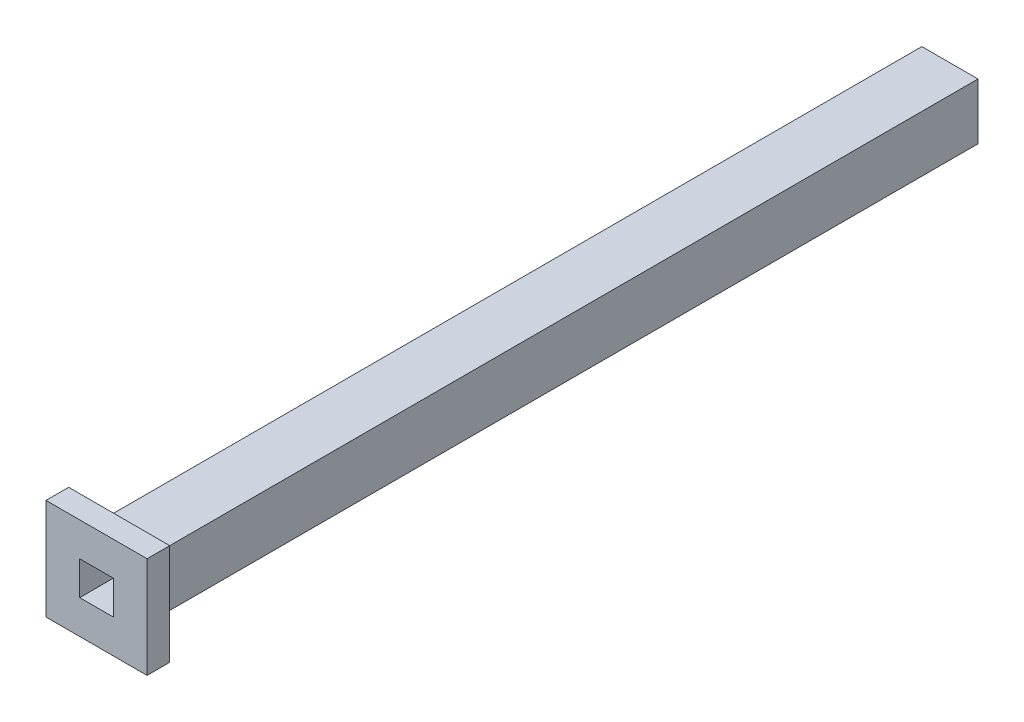
SolidWorks part; units mm, degrees
ref_plane "Front Plane" through (0, 0, 0) normal (0, 0, 1) x (1, 0, 0)
ref_plane "Top Plane" through (0, 0, 0) normal (0, 1, 0) x (1, 0, 0)
ref_plane "Right Plane" through (0, 0, 0) normal (1, 0, 0) x (0, 0, -1)
sketch "Sketch1" plane through (0, 0, 0) normal (0, 0, 1) x (1, 0, 0)
  line L1 (0, 0) -> (6, 0)
  line L2 (0, 0) -> (0, 6)
  line L3 (0, 6) -> (6, 6)
  line L4 (6, 0) -> (6, 6)
  line L5 (-2, 8) -> (8, 8)
  line L6 (-2, 8) -> (-2, -2)
  line L7 (-2, -2) -> (8, -2)
  line L8 (8, 8) -> (8, -2)
  dimension "D1" = 6
  dimension "D2" = 6
  dimension "D3" = 2
  dimension "D4" = 2
  dimension "D5" = 2
  dimension "D6" = 2
extrude "Boss-Extrude1" add sketch "Sketch1" along normal blind 2.54
sketch "Sketch2" plane through (0, 0, 0) normal (0, 0, -1) x (-1, 0, 0)
  line L0 (-8, 8) -> (-8, -2)
  line L1 (-8, -2) -> (2, -2)
  line L2 (2, -2) -> (2, -4)
  line L3 (2, -4) -> (-10, -4)
  line L4 (-10, -4) -> (-10, 8)
  line L5 (-10, 8) -> (-8, 8)
  dimension "D1" = 2
  dimension "D2" = 2
extrude "Boss-Extrude4" add sketch "Sketch2" against normal blind 2.54
sketch "Sketch5" plane through (0, 0, 0) normal (0, 0, -1) x (-1, 0, 0)
  line L0 (-6, 6) -> (-6, 0)
  line L1 (-6, 0) -> (0, 0)
  line L2 (0, 0) -> (0, -2)
  line L3 (0, -2) -> (-8, -2)
  line L4 (-8, -2) -> (-8, 6)
  line L5 (-8, 6) -> (-6, 6)
  dimension "D1" = 2
  dimension "D2" = 2
extrude "Cut-Extrude4" cut sketch "Sketch5" against normal blind 2.54
sketch "Sketch6" plane through (0, 0, 0) normal (0, 0, -1) x (-1, 0, 0)
  line L0 (-10, 8) -> (-10, -4)
  line L1 (-10, -4) -> (2, -4)
  line L2 (2, -4) -> (2, -6)
  line L3 (2, -6) -> (-12, -6)
  line L4 (-12, -6) -> (-12, 8)
  line L5 (-12, 8) -> (-10, 8)
  dimension "D1" = 2
  dimension "D2" = 2
  dimension "D3" = 12
extrude "Boss-Extrude6" add sketch "Sketch6" against normal blind 2.54
sketch "Sketch7" plane through (0, 0, 0) normal (0, 0, -1) x (-1, 0, 0)
  line L0 (-12, 8) -> (2, 8)
  line L1 (2, 8) -> (2, -6)
  line L2 (2, -6) -> (4, -6)
  line L3 (4, -6) -> (4, 10)
  line L4 (4, 10) -> (-12, 10)
  line L5 (-12, 10) -> (-12, 8)
  dimension "D1" = 2
  dimension "D2" = 2
extrude "Boss-Extrude7" add sketch "Sketch7" against normal blind 2.54
sketch "Sketch8" plane through (0, 0, 0) normal (0, 0, -1) x (-1, 0, 0)
  line L0 (-12, 10) -> (4, 10)
  line L1 (4, 10) -> (4, -6)
  line L2 (4, -6) -> (-12, -6)
  line L3 (-12, -6) -> (-12, 10)
  line L5 (-10, 8) -> (2, 8)
  line L6 (-10, 8) -> (-10, -4)
  line L7 (-10, -4) -> (2, -4)
  line L8 (2, 8) -> (2, -4)
  dimension "D1" = 2
  dimension "D2" = 2
  dimension "D3" = 2
  dimension "D4" = 2
extrude "Cut-Extrude5" cut sketch "Sketch8" against normal blind 0.5
sketch "Sketch9" plane through (0, 0, 0) normal (0, 0, -1) x (-1, 0, 0)
  line L1 (-8, 6) -> (0, 6)
  line L2 (-8, 6) -> (-8, -2)
  line L3 (-8, -2) -> (0, -2)
  line L4 (0, 6) -> (0, -2)
extrude "Boss-Extrude8" add sketch "Sketch9" along normal blind 0.5 separate body
sketch "Sketch10" plane through (0, 0, 0) normal (0, 0, -1) x (-1, 0, 0)
  line L1 (-10, 8) -> (2, 8)
  line L2 (-10, 8) -> (-10, -4)
  line L3 (-10, -4) -> (2, -4)
  line L4 (2, 8) -> (2, -4)
  line L5 (-8, 6) -> (0, 6)
  line L6 (-8, 6) -> (-8, -2)
  line L7 (-8, -2) -> (0, -2)
  line L8 (0, 6) -> (0, -2)
extrude "Cut-Extrude6" cut sketch "Sketch10" against normal blind 10
sketch "Sketch11" plane through (0, 0, 2.54) normal (0, 0, 1) x (1, 0, 0)
  line L1 (-4, 10) -> (12, 10)
  line L2 (-4, 10) -> (-4, -6)
  line L3 (-4, -6) -> (12, -6)
  line L4 (12, 10) -> (12, -6)
  line L5 (0, 6) -> (8, 6)
  line L6 (0, 6) -> (0, -2)
  line L7 (0, -2) -> (8, -2)
  line L8 (8, 6) -> (8, -2)
extrude "Boss-Extrude9" add sketch "Sketch11" along normal blind 2
sketch "Sketch13" plane through (0, 0, -0.5) normal (0, 0, -1) x (-1, 0, 0)
  line L1 (-8, 6) -> (0, 6)
  line L2 (-8, 6) -> (-8, -2)
  line L3 (-8, -2) -> (0, -2)
  line L4 (0, 6) -> (0, -2)
extrude "Cut-Extrude7" cut sketch "Sketch13" against normal blind 2
sketch "Sketch14" plane through (0, 0, 2.54) normal (0, 0, -1) x (-1, 0, 0)
  line L5 (-7, 5) -> (-1, 5)
  line L6 (-7, 5) -> (-7, -1)
  line L7 (-7, -1) -> (-1, -1)
  line L8 (-1, 5) -> (-1, -1)
  line L9 (-9, 7) -> (1, 7)
  line L10 (-9, 7) -> (-9, -3)
  line L11 (-9, -3) -> (1, -3)
  line L12 (1, 7) -> (1, -3)
  dimension "D5" = 6
extrude "Cut-Extrude8" cut sketch "Sketch14" against normal blind 2
sketch "Sketch16" plane through (0, 0, 2.54) normal (0, 0, -1) x (-1, 0, 0)
  line L0 (2, 8) -> (2, -4) construction
  line L1 (-10, 8) -> (2, 8)
  line L2 (-10, 8) -> (-10, -4)
  line L3 (-10, -4) -> (2, -4)
  line L4 (2, 8) -> (2, -4)
  line L6 (-11, 9) -> (3, 9)
  line L7 (-11, 9) -> (-11, -5)
  line L8 (-11, -5) -> (3, -5)
  line L9 (3, 9) -> (3, -5)
  dimension "D1" = 1
  dimension "D2" = 1
  dimension "D3" = 1
  dimension "D4" = 1
extrude "Cut-Extrude12" cut sketch "Sketch16" along normal blind 10
sketch "Sketch17" plane through (0, 0, 0.5) normal (0, 0, -1) x (-1, 0, 0)
  line L1 (-12, 10) -> (4, 10)
  line L2 (-12, 10) -> (-12, -6)
  line L3 (-12, -6) -> (4, -6)
  line L4 (4, 10) -> (4, -6)
  line L5 (-13, 11) -> (5, 11)
  line L6 (-13, 11) -> (-13, -7)
  line L7 (-13, -7) -> (5, -7)
  line L8 (5, 11) -> (5, -7)
  dimension "D1" = 1
  dimension "D2" = 1
  dimension "D3" = 1
  dimension "D4" = 1
extrude "Boss-Extrude10" add sketch "Sketch17" against normal blind 4
sketch "Sketch18" plane through (0, 0, 4.54) normal (0, 0, 1) x (1, 0, 0)
  line L1 (-4, 10) -> (12, 10)
  line L2 (-4, 10) -> (-4, -6)
  line L3 (-4, -6) -> (12, -6)
  line L4 (12, 10) -> (12, -6)
  line L5 (-5, 11) -> (13, 11)
  line L6 (-5, 11) -> (-5, -7)
  line L7 (-5, -7) -> (13, -7)
  line L8 (13, 11) -> (13, -7)
extrude "Boss-Extrude11" add sketch "Sketch18" against normal blind 1
sketch "Sketch19" plane through (0, 0, 4.54) normal (0, 0, 1) x (1, 0, 0)
  line L1 (-1, 7) -> (9, 7)
  line L2 (-1, 7) -> (-1, -3)
  line L3 (-1, -3) -> (9, -3)
  line L4 (9, 7) -> (9, -3)
  line L5 (1, 5) -> (7, 5)
  line L6 (1, 5) -> (1, -1)
  line L7 (1, -1) -> (7, -1)
  line L8 (7, 5) -> (7, -1)
  dimension "D1" = 2
  dimension "D2" = 2
  dimension "D3" = 2
  dimension "D4" = 2
extrude "Boss-Extrude12" add sketch "Sketch19" against normal blind 150
sketch "Sketch20" plane through (0, 0, -145.46) normal (0, 0, -1) x (-1, 0, 0)
  line L0 (1, -3) -> (1, 7) construction
  line L1 (-9, 7) -> (1, 7)
  line L2 (-9, 7) -> (-9, -3)
  line L3 (-9, -3) -> (1, -3)
  line L4 (1, 7) -> (1, -3)
extrude "Boss-Extrude13" add sketch "Sketch20" along normal blind 2
